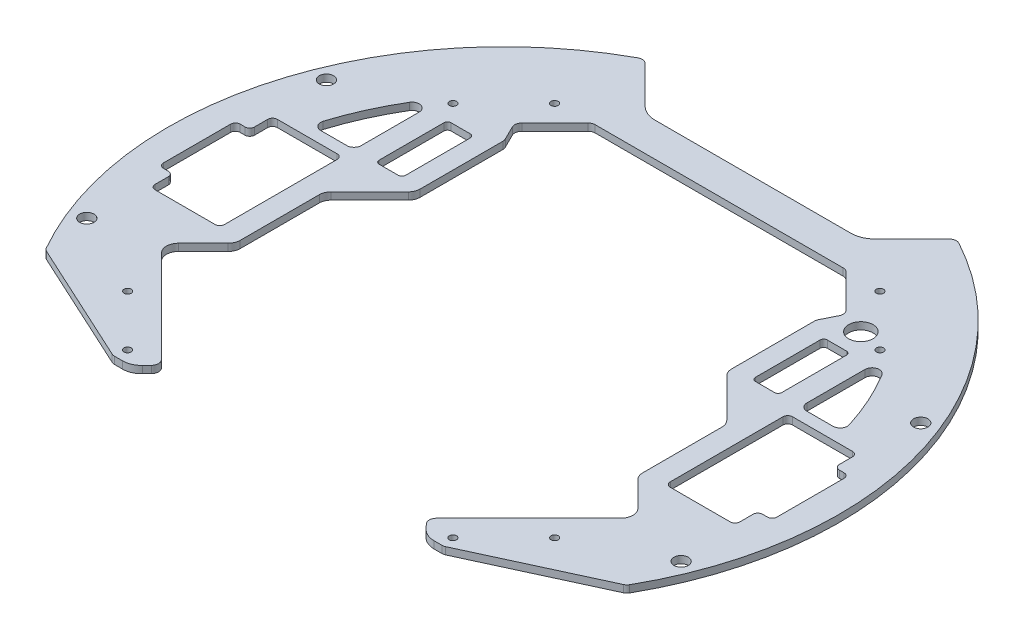
SolidWorks part; units mm, degrees
material "1060 Alloy"
ref_plane "Front Plane" through (0, 0, 0) normal (0, 0, 1) x (1, 0, 0)
ref_plane "Top Plane" through (0, 0, 0) normal (0, 1, 0) x (1, 0, 0)
ref_plane "Right Plane" through (0, 0, 0) normal (1, 0, 0) x (0, 0, -1)
sketch "Sketch1" plane through (0, 0, 0) normal (0, 1, 0) x (1, 0, 0)
  circle A0 centre (0, 0) radius 140
  dimension "D1" = 280
extrude "Boss-Extrude1" add sketch "Sketch1" along normal blind 3
sketch "Sketch19" plane through (0, 3, 0) normal (0, 1, 0) x (1, 0, 0)
  line L0 (-78.4889, 78.4889) -> (78.4889, -78.4889) construction
  line L1 (111, 45.9777) -> (45.9777, 111) construction
  line L2 (45.9777, 111) -> (-45.9777, 111) construction
  line L3 (-45.9777, 111) -> (-111, 45.9777) construction
  line L4 (-111, 45.9777) -> (-111, -45.9777) construction
  line L5 (-111, -45.9777) -> (-45.9777, -111) construction
  line L6 (-45.9777, -111) -> (45.9777, -111) construction
  line L7 (45.9777, -111) -> (111, -45.9777) construction
  line L8 (111, -45.9777) -> (111, 45.9777) construction
  line L9 (78.4889, 78.4889) -> (-78.4889, -78.4889) construction
  circle A0 centre (-89.0955, -67.8823) radius 1.5
  circle A1 centre (-89.0955, 67.8823) radius 1.5
  circle A2 centre (89.0955, 67.8823) radius 1.5
  circle A3 centre (89.0955, -67.8823) radius 1.5
  circle A4 centre (0, 0) radius 111 construction
  circle A5 centre (-67.8823, -89.0955) radius 1.5
  circle A6 centre (67.8823, 89.0955) radius 1.5
  circle A7 centre (-67.8823, 89.0955) radius 1.5
  circle A8 centre (67.8823, -89.0955) radius 1.5
  dimension "D5" = 3
  dimension "D1" = 15
  dimension "D2" = 15
  dimension "D6" = 111
extrude "Cut-Extrude3" cut sketch "Sketch19" against normal up to next
sketch "Sketch17" plane through (0, 0, 0) normal (0, -1, 0) x (1, 0, 0)
  line L0 (-68.9793, 94.0955) -> (-121.2436, 70)
  line L1 (-68.9793, 94.0955) -> (68.9793, 94.0955)
  line L2 (-121.2436, 70) -> (-121.2436, 140)
  line L3 (-121.2436, 140) -> (121.2436, 140)
  line L4 (121.2436, 140) -> (121.2436, 70)
  line L5 (121.2436, 70) -> (68.9793, 94.0955)
  circle A0 centre (0, 0) radius 140 construction
  circle A1 centre (67.8823, 89.0955) radius 5 construction
  circle A2 centre (-67.8823, 89.0955) radius 5 construction
  dimension "D1" = 10
  dimension "D4" = 70
extrude "Cut-Extrude1" cut sketch "Sketch17" against normal up to next
sketch "Sketch20" plane through (0, 3, 0) normal (0, 1, 0) x (1, 0, 0)
  line L0 (-65, 123.996) -> (-45, 103.996)
  line L1 (-45, 103.996) -> (45, 103.996)
  line L2 (45, 103.996) -> (65, 123.996)
  arc A1 (121.2436, -70) -> (-121.2436, -70) centre (0, 0) ccw construction
  dimension "D1" = 130
  dimension "D2" = 90
  dimension "D3" = 45
extrude "Cut-Extrude4" cut sketch "Sketch20" against normal up to next
sketch "Sketch21" plane through (0, 3, 0) normal (0, 1, 0) x (1, 0, 0)
  line L0 (-52.9668, 89.8688) -> (0, 60)
  line L1 (0, 60) -> (52.9668, 89.8688)
  line L2 (69.1558, 73.6797) -> (40, 15)
  line L3 (40, 15) -> (70.5019, -72.3336)
  line L4 (62.1139, -94.6385) -> (0, -30) construction
  line L5 (0, -30) -> (-62.1139, -94.6385) construction
  line L6 (-70.5019, -72.3336) -> (-40, 15)
  line L7 (-40, 15) -> (-69.1558, 73.6797)
  line L8 (-69.1558, 73.6797) -> (-52.9668, 89.8688)
  line L9 (52.9668, 89.8688) -> (69.1558, 73.6797)
  line L10 (-55.294, -87.5415) -> (-59.231, -91.6385)
  line L11 (-68.9793, -94.0955) -> (68.9793, -94.0955) construction
  line L12 (-78.4889, 78.4889) -> (78.4889, -78.4889) construction
  line L13 (111, 45.9777) -> (45.9777, 111) construction
  line L14 (45.9777, 111) -> (-45.9777, 111) construction
  line L15 (-45.9777, 111) -> (-111, 45.9777) construction
  line L16 (-111, 45.9777) -> (-111, -45.9777) construction
  line L17 (-111, -45.9777) -> (-45.9777, -111) construction
  line L18 (-45.9777, -111) -> (45.9777, -111) construction
  line L19 (45.9777, -111) -> (111, -45.9777) construction
  line L20 (111, -45.9777) -> (111, 45.9777) construction
  line L21 (78.4889, 78.4889) -> (-78.4889, -78.4889) construction
  line L22 (-55.294, -87.5415) -> (-70.5019, -72.3336)
  line L25 (55.294, -87.5415) -> (70.5019, -72.3336)
  line L26 (-69.1558, 73.6797) -> (-75.0466, 85.5357) construction
  line L27 (-63.9527, 96.0638) -> (-52.9668, 89.8688) construction
  line L28 (52.9668, 89.8688) -> (63.9527, 96.0638) construction
  line L29 (75.0466, 85.5357) -> (69.1558, 73.6797) construction
  line L30 (-64.9994, -94.0955) -> (64.9994, -94.0955)
  line L34 (59.231, -91.6385) -> (55.294, -87.5415)
  arc A0 (-75.0466, 85.5357) -> (-63.9527, 96.0638) centre (-67.8823, 89.0955) cw construction
  arc A1 (63.9527, 96.0638) -> (75.0466, 85.5357) centre (67.8823, 89.0955) cw construction
  arc A2 (-62.1139, -94.6385) -> (-75.5411, -86.784) centre (-67.8823, -89.0955) cw construction
  arc A3 (75.5411, -86.784) -> (62.1139, -94.6385) centre (67.8823, -89.0955) cw construction
  arc A4 (-59.231, -91.6385) -> (-64.9994, -94.0955) centre (-64.9994, -86.0955) cw
  circle A5 centre (0, 0) radius 111 construction
  arc A6 (59.231, -91.6385) -> (64.9994, -94.0955) centre (64.9994, -86.0955) ccw
  ellipse E0 centre (0, 15) end of major axis (0, 60) minor radius 40 construction
  dimension "D1" = 40
  dimension "D2" = 8
  dimension "D3" = 15
  dimension "D4" = 15
  dimension "D5" = 45
  dimension "D6" = 10
  dimension "D7" = 10
  dimension "D8" = 111
  dimension "D9" = 10
  dimension "D14" = 10
extrude "Cut-Extrude5" cut sketch "Sketch21" against normal up to next
fillet "Fillet1" radius 20 3 edges at (40, 1.5, -15) (-40, 1.5, -15) (0, 1.5, -60)
fillet "Fillet2" radius 10 2 edges at (45, 1.5, -103.996) (-45, 1.5, -103.996)
sketch "Sketch22" plane through (0, 3, 0) normal (0, 1, 0) x (1, 0, 0)
  line L1 (93, 25.5) -> (122, 25.5)
  line L2 (93, 25.5) -> (93, -25.5)
  line L3 (93, -25.5) -> (122, -25.5)
  line L4 (122, 25.5) -> (122, -25.5)
  line L5 (-122, 25.5) -> (-93, 25.5)
  line L6 (-122, 25.5) -> (-122, -25.5)
  line L7 (-122, -25.5) -> (-93, -25.5)
  line L8 (-93, 25.5) -> (-93, -25.5)
  dimension "D1" = 93
  dimension "D2" = 93
  dimension "D4" = 51
  dimension "D5" = 29
  dimension "D7" = 25.5
extrude "Cut-Extrude6" cut sketch "Sketch22" against normal up to next
sketch "Sketch31" plane through (0, 3, 0) normal (0, 1, 0) x (1, 0, 0)
  line L1 (-128, 16) -> (-122, 16)
  line L2 (-128, 16) -> (-128, -16)
  line L3 (-128, -16) -> (-122, -16)
  line L4 (-122, 16) -> (-122, -16)
  line L6 (128, 16) -> (122, 16)
  line L7 (128, 16) -> (128, -16)
  line L8 (128, -16) -> (122, -16)
  line L9 (122, 16) -> (122, -16)
  line L11 (122, -25.5) -> (122, 25.5) construction
  line L12 (-122, 25.5) -> (-122, -25.5) construction
  line L13 (93, 25.5) -> (93, -25.5) construction
  dimension "D1" = 32
  dimension "D2" = 35
  dimension "D3" = 16
extrude "Cut-Extrude15" cut sketch "Sketch31" against normal up to next
fillet "Fillet3" radius 2 16 edges at (122, 1.5, 25.5) (93, 1.5, 25.5) (93, 1.5, -25.5) (122, 1.5, -25.5) (-93, 1.5, 25.5) (-122, 1.5, 25.5) (-93, 1.5, -25.5) (-122, 1.5, -25.5) (-122, 1.5, -16) (-128, 1.5, -16) (-122, 1.5, 16) (-128, 1.5, 16) (128, 1.5, -16) (122, 1.5, -16) (128, 1.5, 16) (122, 1.5, 16)
sketch "Sketch23" plane through (0, 3, 0) normal (0, 1, 0) x (1, 0, 0)
  circle A0 centre (-124, 50) radius 3
  circle A1 centre (-124, -50) radius 3
  circle A2 centre (124, -50) radius 3
  circle A3 centre (124, 50) radius 3
  dimension "D1" = 6
  dimension "D2" = 124
  dimension "D3" = 124
  dimension "D4" = 50
  dimension "D5" = 50
extrude "Cut-Extrude7" cut sketch "Sketch23" against normal up to next
sketch "Sketch24" plane through (0, 3, 0) normal (0, 1, 0) x (1, 0, 0)
  line L0 (-93, 57.6888) -> (-93, 30.5)
  line L1 (-93, 30.5) -> (-110.8817, 30.5)
  line L2 (-95, 25.5) -> (-120, 25.5) construction
  arc A0 (-110.8817, 30.5) -> (-98.5714, 59.2341) centre (0, 0) cw
  arc A1 (-98.5714, 59.2341) -> (-93, 57.6888) centre (-96, 57.6888) cw
  arc A2 (-65, 123.996) -> (-121.2436, -70) centre (0, 0) ccw construction
  dimension "D3" = 25
  dimension "D4" = 3
  dimension "D1" = 5
  dimension "D2" = 93
extrude "Cut-Extrude8" cut sketch "Sketch24" against normal up to next
fillet "Fillet4" radius 3 2 edges at (-93, 1.5, -30.5) (-110.8817, 1.5, -30.5)
mirror "Mirror1" about plane through (0, 0, 0) normal (1, 0, 0) of "Fillet4", "Cut-Extrude8"
sketch "Sketch26" plane through (0, 3, 0) normal (0, 1, 0) x (1, 0, 0)
  line L0 (55.294, -87.5415) -> (70.5019, -72.3336) construction
  line L2 (-65, 77.8356) -> (-65, -77.8356)
  line L3 (69.1558, 73.6797) -> (52.9668, 89.8688) construction
  line L5 (-65, 77.8356) -> (65, 77.8356)
  line L8 (65, 77.8356) -> (65, -77.8356)
  line L11 (65, -77.8356) -> (-65, -77.8356)
  dimension "D2" = 65
  dimension "D1" = 65
extrude "Cut-Extrude10" cut sketch "Sketch26" against normal up to next
sketch "Sketch27" plane through (0, 3, 0) normal (0, 1, 0) x (1, 0, 0)
  line L0 (-52.9668, 89.8688) -> (-69.1558, 73.6797) construction
  line L1 (-52.9668, 89.8688) -> (52.9668, 89.8688)
  line L2 (69.1558, 73.6797) -> (52.9668, 89.8688) construction
  line L3 (-52.9668, 77.8356) -> (52.9668, 77.8356)
  line L4 (31.6281, 77.8356) -> (-31.6281, 77.8356) construction
  line L5 (-31.6281, 77.8356) -> (-52.9668, 89.8688) construction
  line L8 (-52.9668, 77.8356) -> (-52.9668, 89.8688)
  line L9 (52.9668, 77.8356) -> (52.9668, 89.8688)
extrude "Cut-Extrude11" cut sketch "Sketch27" against normal up to next
fillet "Fillet5" radius 3 18 edges at (-65, 1.5, -123.996) (65, 1.5, -123.996) (121.2436, 1.5, 70) (-121.2436, 1.5, 70) (55.294, 1.5, 87.5415) (-55.294, 1.5, 87.5415) (52.9668, 1.5, -89.8688) (-52.9668, 1.5, -89.8688) (-68.9793, 1.5, 94.0955) (68.9793, 1.5, 94.0955) (-70.5019, 1.5, 72.3336) (70.5019, 1.5, 72.3336) (-65, 1.5, -65.3156) (-69.1558, 1.5, -73.6797) (69.1558, 1.5, -73.6797) (65, 1.5, -65.3156) (65, 1.5, 56.5804) (-65, 1.5, 56.5804)
sketch "Sketch32" plane through (0, 3, 0) normal (0, 1, 0) x (1, 0, 0)
  line L1 (-84, 60.5) -> (-73, 60.5)
  line L2 (-84, 60.5) -> (-84, 30.5)
  line L3 (-84, 30.5) -> (-73, 30.5)
  line L4 (-73, 60.5) -> (-73, 30.5)
  line L5 (-65, 64.6114) -> (-65, -56.0716) construction
  line L6 (-106.8726, 30.5) -> (-96, 30.5) construction
  dimension "D1" = 11
  dimension "D2" = 30
  dimension "D4" = 8
extrude "Cut-Extrude16" cut sketch "Sketch32" against normal up to next
fillet "Fillet7" radius 1.5 4 edges at (-73, 1.5, -30.5) (-84, 1.5, -30.5) (-84, 1.5, -60.5) (-73, 1.5, -60.5)
mirror "Mirror2" about plane through (0, 0, 0) normal (1, 0, 0) of "Cut-Extrude16", "Fillet7"
sketch "Sketch29" plane through (0, 3, 0) normal (0, 1, 0) x (1, 0, 0)
  line L1 (65, -56.0716) -> (65, 64.6114) construction
  line L3 (74.5, 60.5) -> (82.5, 60.5) construction
  circle A0 centre (78.5, 70.5) radius 5.1
  dimension "D1" = 10.2
  dimension "D2" = 13.5
  dimension "D3" = 10
extrude "Cut-Extrude13" cut sketch "Sketch29" against normal up to next
sketch "Sketch34" plane through (0, 3, 0) normal (0, 1, 0) x (1, 0, 0)
  line L0 (-65, 28.065) -> (-84, 9.065)
  line L1 (-65, 64.6114) -> (-65, -56.0716) construction
  line L2 (-84, 9.065) -> (-84, -28.0563)
  line L3 (-84, -28.0563) -> (-99.3896, -43.446)
  line L4 (-99.3896, -43.446) -> (-65, -77.8356)
  line L5 (-69.1699, -73.6657) -> (-57.3735, -85.462) construction
  line L6 (-65, -77.8356) -> (-65, 28.065)
  line L8 (-93, -23.5) -> (-93, 23.5) construction
  circle A0 centre (-74.5, 32) radius 9.5 construction
  circle A1 centre (-95, -23.5) radius 11 construction
  dimension "D2" = 9
extrude "Cut-Extrude17" cut sketch "Sketch34" against normal up to next
mirror "Mirror3" about plane through (0, 0, 0) normal (1, 0, 0) of "Cut-Extrude17"
fillet "Fillet8" radius 5 8 edges at (-99.3896, 1.5, 43.446) (-84, 1.5, 28.0563) (-84, 1.5, -9.065) (-65, 1.5, -28.065) (99.3896, 1.5, 43.446) (84, 1.5, 28.0563) (84, 1.5, -9.065) (65, 1.5, -28.065)
equation "\"D3@Sketch20\" = \"D2@Sketch20\" / 2"
